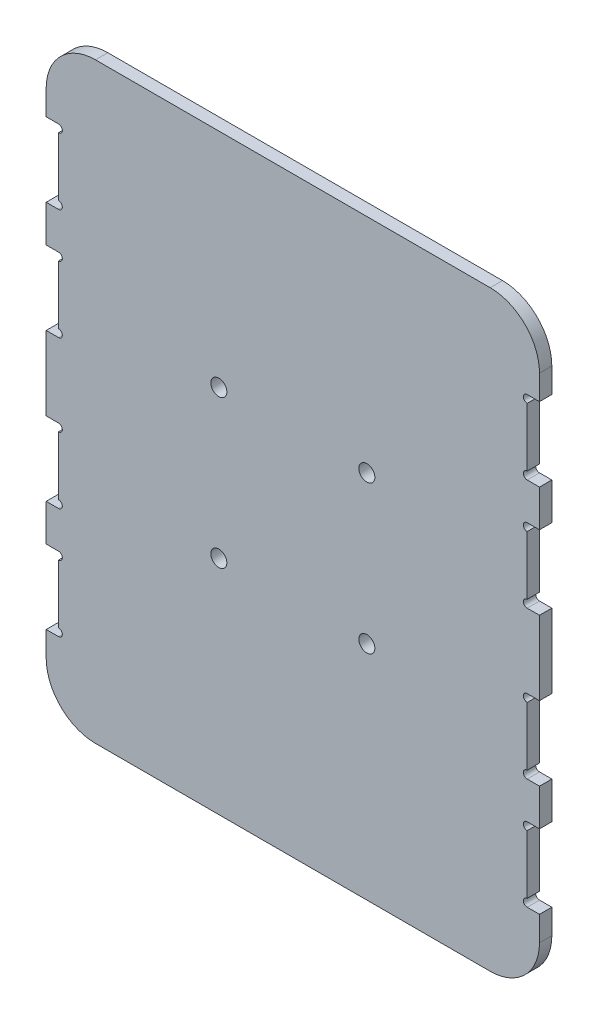
SolidWorks part; units mm, degrees
ref_plane "前视基准面" through (0, 0, 0) normal (0, 0, 1) x (1, 0, 0)
ref_plane "上视基准面" through (0, 0, 0) normal (0, 1, 0) x (1, 0, 0)
ref_plane "右视基准面" through (0, 0, 0) normal (1, 0, 0) x (0, 0, -1)
other "Configuration Table"
sketch "草图1" plane through (0, 0, 0) normal (0, 0, 1) x (1, 0, 0)
  line L0 (0, 0) -> (284.1069, 0) construction
  line L1 (-100, 120) -> (100, 120)
  line L2 (-100, 120) -> (-100, -120)
  line L3 (-100, -120) -> (100, -120)
  line L4 (100, 120) -> (100, -120)
  line L5 (0, 0) -> (0, 194.938) construction
  circle A0 centre (30, 30) radius 3.25
  circle A1 centre (30, -30) radius 3.25
  circle A2 centre (-30, 30) radius 3.25
  circle A3 centre (-30, -30) radius 3.25
  dimension "D3" = 6.5
  dimension "D1" = 240
  dimension "D2" = 200
  dimension "D4" = 30
  dimension "D5" = 30
extrude "凸台-拉伸1" add sketch "草图1" along normal blind 5
fillet "圆角1" radius 20 4 edges at (-100, 120, 2.5) (-100, -120, 2.5) (100, -120, 2.5) (100, 120, 2.5)
sketch "草图3" plane through (0, 0, 5) normal (0, 0, 1) x (1, 0, 0)
  line L0 (0, 126.8429) -> (0, -134.2378) construction
  line L1 (-131.0539, 0) -> (117.702, 0) construction
  line L2 (100, 100) -> (100, -100) construction
  line L3 (95, 90) -> (100, 90)
  line L4 (95, 90) -> (95, 60)
  line L5 (95, 60) -> (100, 60)
  line L6 (100, 90) -> (100, 60)
  line L7 (100, -45) -> (100, -15)
  line L8 (95, 45) -> (100, 45)
  line L9 (95, 45) -> (95, 15)
  line L10 (95, 15) -> (100, 15)
  line L11 (100, 45) -> (100, 15)
  line L12 (95, -15) -> (100, -15)
  line L13 (95, -45) -> (95, -15)
  line L14 (95, -45) -> (100, -45)
  line L15 (100, -90) -> (100, -60)
  line L16 (95, -60) -> (100, -60)
  line L17 (95, -90) -> (95, -60)
  line L18 (95, -90) -> (100, -90)
  line L19 (-95, -90) -> (-100, -90)
  line L20 (-95, -90) -> (-95, -60)
  line L21 (-95, -60) -> (-100, -60)
  line L22 (-100, -90) -> (-100, -60)
  line L23 (-95, -45) -> (-100, -45)
  line L24 (-95, -45) -> (-95, -15)
  line L25 (-95, -15) -> (-100, -15)
  line L26 (-100, 45) -> (-100, 15)
  line L27 (-95, 15) -> (-100, 15)
  line L28 (-95, 45) -> (-95, 15)
  line L29 (-95, 45) -> (-100, 45)
  line L30 (-100, -45) -> (-100, -15)
  line L31 (-100, 90) -> (-100, 60)
  line L32 (-95, 60) -> (-100, 60)
  line L33 (-95, 90) -> (-95, 60)
  line L34 (-95, 90) -> (-100, 90)
  dimension "D1" = 5
  dimension "D2" = 5
  dimension "D3" = 15
  dimension "D4" = 30
  dimension "D5" = 15
  dimension "D6" = 30
extrude "切除-拉伸1" cut sketch "草图3" against normal blind 39
sketch "草图4" plane through (0, 0, 5) normal (0, 0, 1) x (1, 0, 0)
  line L0 (0, 0) -> (0, 131.5675) construction
  line L1 (95, 90) -> (95, 60) construction
  line L2 (95, 45) -> (95, 15) construction
  line L3 (95, -15) -> (95, -45) construction
  line L4 (95, -60) -> (95, -90) construction
  line L5 (100, 90) -> (95, 90) construction
  line L6 (95, 60) -> (100, 60) construction
  line L7 (100, 45) -> (95, 45) construction
  line L8 (95, 15) -> (100, 15) construction
  line L9 (100, -15) -> (95, -15) construction
  line L10 (95, -45) -> (100, -45) construction
  line L11 (100, -60) -> (95, -60) construction
  line L12 (95, -90) -> (100, -90) construction
  circle A0 centre (95, 88.45) radius 1.55
  circle A1 centre (95, 61.55) radius 1.55
  circle A2 centre (95, 43.45) radius 1.55
  circle A3 centre (95, 16.55) radius 1.55
  circle A4 centre (95, -16.55) radius 1.55
  circle A5 centre (95, -43.45) radius 1.55
  circle A6 centre (95, -61.55) radius 1.55
  circle A7 centre (95, -88.45) radius 1.55
  circle A8 centre (-95, -88.45) radius 1.55
  circle A9 centre (-95, -61.55) radius 1.55
  circle A10 centre (-95, -43.45) radius 1.55
  circle A11 centre (-95, -16.55) radius 1.55
  circle A12 centre (-95, 16.55) radius 1.55
  circle A13 centre (-95, 43.45) radius 1.55
  circle A14 centre (-95, 61.55) radius 1.55
  circle A15 centre (-95, 88.45) radius 1.55
  dimension "D1" = 3.1
extrude "切除-拉伸2" cut sketch "草图4" against normal up to surface (5 mm away) up to face at (0, 0, 0)
